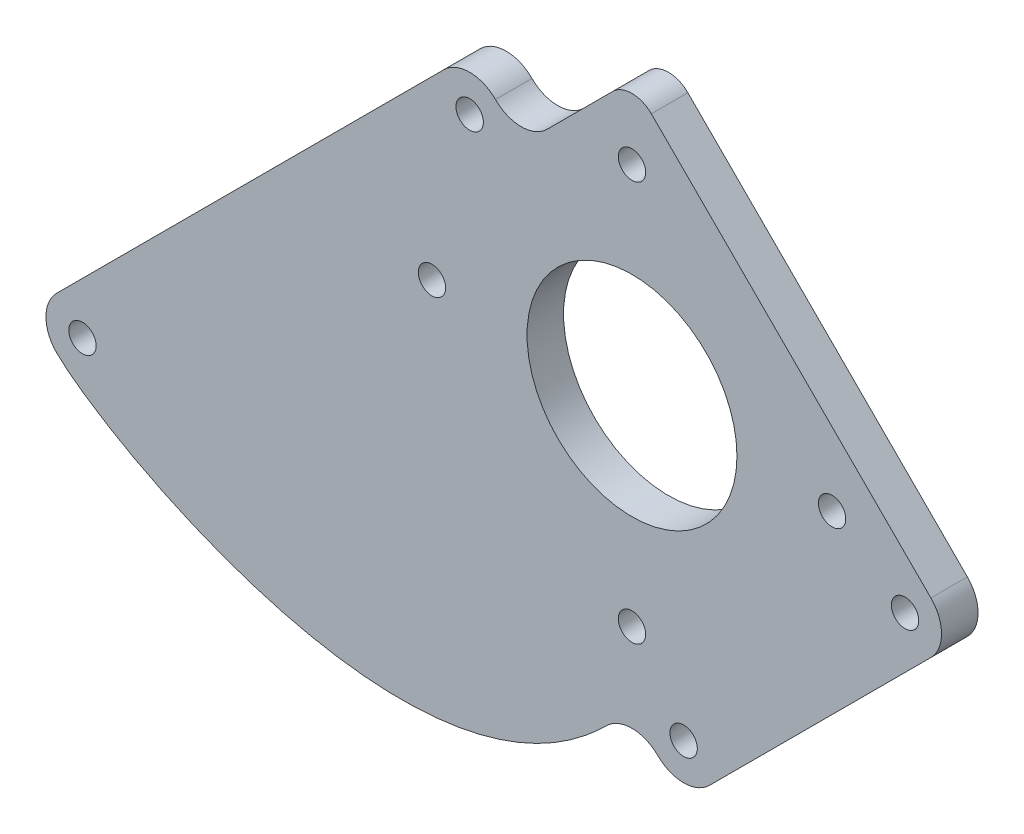
SolidWorks part; units mm, degrees
ref_plane "Front Plane" through (0, 0, 0) normal (0, 0, 1) x (1, 0, 0)
ref_plane "Top Plane" through (0, 0, 0) normal (0, 1, 0) x (1, 0, 0)
ref_plane "Right Plane" through (0, 0, 0) normal (1, 0, 0) x (0, 0, -1)
sketch "Sketch1" plane through (0, 0, 0) normal (0, 0, 1) x (1, 0, 0)
  line L0 (0, -29.9184) -> (0, 29.9184) construction
  line L1 (0, 21.9203) -> (-21.9203, 0) construction
  line L2 (0, 21.9203) -> (21.9203, 0) construction
  line L3 (-21.9203, 0) -> (0, -21.9203) construction
  line L4 (21.9203, 0) -> (0, -21.9203) construction
  line L5 (0, 21.9203) -> (0, -21.9203) construction
  line L6 (-21.9203, 0) -> (21.9203, 0) construction
  line L7 (0, 29.9184) -> (-29.9184, 0) construction
  line L8 (-29.9184, 0) -> (29.9184, 0) construction
  line L9 (0, 29.9184) -> (29.9184, 0) construction
  line L10 (-29.9184, 0) -> (0, -29.9184) construction
  line L11 (29.9184, 0) -> (0, -29.9184) construction
  line L20 (-60.2141, -24.6388) -> (-17.7876, 17.7876) construction
  line L21 (5.6569, -29.9184) -> (29.9184, -5.6569) construction
  line L22 (14.9592, -14.9592) -> (-14.9592, 14.9592) construction
  line L23 (29.9184, 0) -> (0, 29.9184) construction
  line L24 (-20.6161, 20.6161) -> (-63.0425, -21.8103)
  line L25 (-60.2141, -24.6388) -> (-63.0425, -21.8103) construction
  line L26 (32.7469, -8.4853) -> (8.4853, -32.7469)
  line L27 (5.6569, -29.9184) -> (8.4853, -32.7469) construction
  line L28 (29.9184, -5.6569) -> (32.7469, -8.4853) construction
  line L29 (-17.7876, 17.7876) -> (-20.6161, 20.6161) construction
  line L30 (29.9184, -5.6569) -> (32.7469, -2.8284) construction
  line L31 (32.7469, -2.8284) -> (35.5753, 0) construction
  line L32 (32.7469, 2.8284) -> (29.9184, 0) construction
  line L34 (-17.7876, 17.7876) -> (-12.1308, 23.4445) construction
  line L35 (0, 29.9184) -> (-9.3024, 20.6161)
  line L36 (-60.2141, -24.6388) -> (-63.0425, -27.4672) construction
  line L39 (0, 29.9184) -> (32.7469, -2.8284)
  circle A0 centre (29.9184, -5.6569) radius 1.5
  circle A1 centre (-21.9203, 0) radius 1.5
  circle A2 centre (0, 21.9203) radius 1.5
  circle A3 centre (21.9203, 0) radius 1.5
  circle A7 centre (0, 0) radius 11.5
  circle A9 centre (0, -21.9203) radius 1.5
  circle A10 centre (5.6569, -29.9184) radius 1.5
  circle A11 centre (-17.7876, 17.7876) radius 1.5
  circle A12 centre (-60.2141, -24.6388) radius 1.5
  arc A13 (32.7469, -8.4853) -> (32.7469, -2.8284) centre (29.9184, -5.6569) ccw
  arc A14 (32.7469, -2.8284) -> (32.7469, 2.8284) centre (35.5753, 0) cw construction
  arc A15 (2.8284, -32.7469) -> (-2.8284, -32.7469) centre (0, -35.5753) ccw
  arc A16 (8.4853, -32.7469) -> (2.8284, -32.7469) centre (5.6569, -29.9184) cw
  arc A17 (-20.6161, 20.6161) -> (-14.9592, 20.6161) centre (-17.7876, 17.7876) cw
  arc A18 (-14.9592, 20.6161) -> (-9.3024, 20.6161) centre (-12.1308, 23.4445) ccw
  arc A19 (-63.0425, -21.8103) -> (-63.0425, -27.4672) centre (-60.2141, -24.6388) ccw
  spline S0 degree 3 poles (-2.8284, -32.7469) (-22.7447, -52.5905) (-57.2682, -33.2018) (-63.0425, -27.4672) knots 0 0 0 0 1 1 1 1
  point P4 (0, 0)
  point P6 (0, 0)
  point P15 (0, 0)
  point P32 (17.7876, -17.7876)
  dimension "D2" = 3
  dimension "D3" = 23
  dimension "D1" = 31
  dimension "D4" = 5.6555
  dimension "D5" = 60
  dimension "D6" = 4
  dimension "D7" = 4
  dimension "D8" = 4
  dimension "D9" = 4
  dimension "D10" = 4
  dimension "D11" = 4
  dimension "D12" = 8
extrude "Boss-Extrude1" add sketch "Sketch1" along normal blind 4
fillet "Fillet1" radius 3 1 edges at (0, 29.9184, 2)
